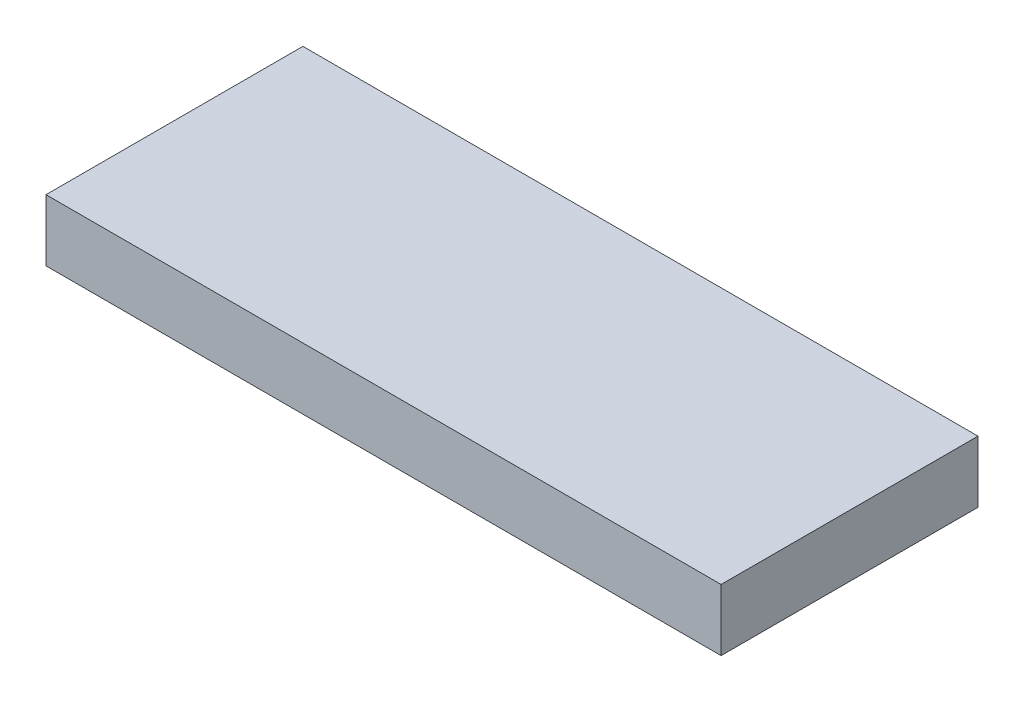
SolidWorks part; units mm, degrees
ref_plane "前视基准面" through (0, 0, 0) normal (0, 0, 1) x (1, 0, 0)
ref_plane "上视基准面" through (0, 0, 0) normal (0, 1, 0) x (1, 0, 0)
ref_plane "右视基准面" through (0, 0, 0) normal (1, 0, 0) x (0, 0, -1)
sketch "草图1" plane through (0, 0, 0) normal (0, 0, 1) x (1, 0, 0)
  line L1 (-19.71, 3.6) -> (19.71, 3.6)
  line L2 (-19.71, 3.6) -> (-19.71, 0)
  line L3 (-19.71, 0) -> (19.71, 0)
  line L4 (19.71, 3.6) -> (19.71, 0)
  dimension "D1" = 39.42
  dimension "D2" = 19.71
  dimension "D3" = 3.6
extrude "凸台-拉伸1" add sketch "草图1" along normal blind 15
